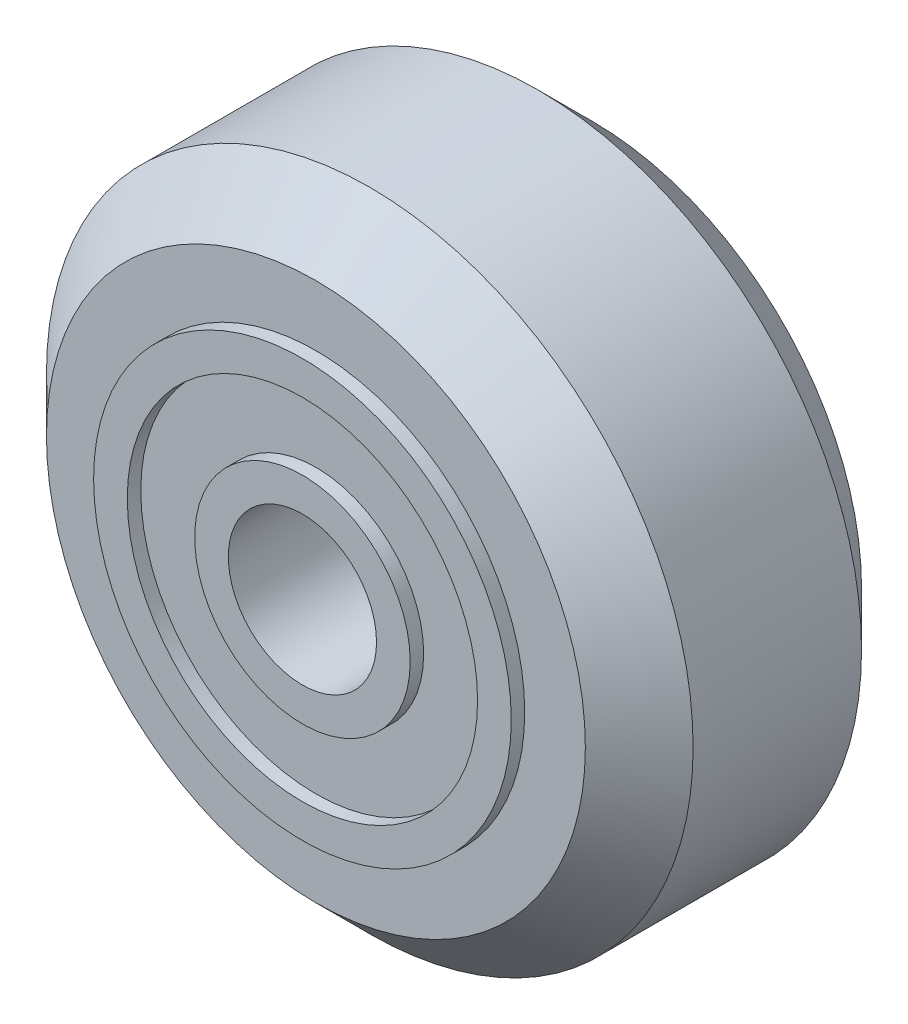
SolidWorks part; units mm, degrees
ref_plane "Front Plane" through (0, 0, 0) normal (0, 0, 1) x (1, 0, 0)
ref_plane "Top Plane" through (0, 0, 0) normal (0, 1, 0) x (1, 0, 0)
ref_plane "Right Plane" through (0, 0, 0) normal (1, 0, 0) x (0, 0, -1)
sketch "Sketch1" plane through (0, 0, 0) normal (0, 0, 1) x (1, 0, 0)
  circle A0 centre (0, 0) radius 12
  circle A1 centre (0, 0) radius 7.75
  dimension "D1" = 24
  dimension "D2" = 15.5
extrude "Boss-Extrude1" add sketch "Sketch1" along normal mid plane 10.25
chamfer "Chamfer1" distance 2 angle 45 2 edges at (12, 0, -5.125) (12, 0, 5.125)
sketch "Sketch2" plane through (0, 0, 5.125) normal (0, 0, 1) x (1, 0, 0)
  circle A0 centre (0, 0) radius 7.75
  circle A1 centre (0, 0) radius 6.5
  circle A3 centre (0, 0) radius 7.75 construction
  dimension "D1" = 1.25
extrude "Boss-Extrude2" add sketch "Sketch2" along normal blind 0.5 and the other way blind 10.5
sketch "Sketch3" plane through (0, 0, 5.125) normal (0, 0, 1) x (1, 0, 0)
  circle A0 centre (0, 0) radius 6.5
  circle A1 centre (0, 0) radius 6.5 construction
  circle A2 centre (0, 0) radius 4
  dimension "D1" = 2.5
extrude "Boss-Extrude3" add sketch "Sketch3" against normal up to surface (10.25 mm away) up to face at (10, 0, -5.125)
sketch "Sketch4" plane through (0, 0, 5.625) normal (0, 0, 1) x (1, 0, 0)
  line L0 (6.5, 0) -> (7.75, 0) construction
  line L1 (2.75, 0) -> (4, 0) construction
  circle A0 centre (0, 0) radius 4
  circle A1 centre (0, 0) radius 4 construction
  circle A2 centre (0, 0) radius 2.75
  circle A3 centre (0, 0) radius 6.5 construction
  circle A4 centre (0, 0) radius 6.5 construction
  circle A5 centre (0, 0) radius 7.75 construction
extrude "Boss-Extrude4" add sketch "Sketch4" against normal up to surface (11 mm away) up to face at (6.5, 0, -5.375)
